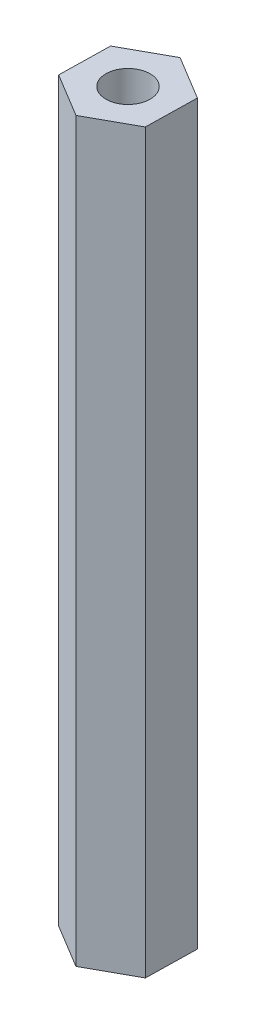
SolidWorks part; units mm, degrees
ref_plane "前视基准面" through (0, 0, 0) normal (0, 0, 1) x (1, 0, 0)
ref_plane "上视基准面" through (0, 0, 0) normal (0, 1, 0) x (1, 0, 0)
ref_plane "右视基准面" through (0, 0, 0) normal (1, 0, 0) x (0, 0, -1)
sketch "草图1" plane through (0, 0, 0) normal (0, 1, 0) x (1, 0, 0)
  line L1 (2.9659, -1.7898) -> (3.033, 1.6737)
  line L2 (3.033, 1.6737) -> (0.067, 3.4635)
  line L3 (0.067, 3.4635) -> (-2.9659, 1.7898)
  line L4 (-2.9659, 1.7898) -> (-3.033, -1.6737)
  line L5 (-3.033, -1.6737) -> (-0.067, -3.4635)
  line L6 (-0.067, -3.4635) -> (2.9659, -1.7898)
  circle A0 centre (0, 0) radius 3 construction
  circle A1 centre (0, 0) radius 1.5
  dimension "D1" = 6
  dimension "D2" = 3
extrude "凸台-拉伸1" add sketch "草图1" along normal blind 50
